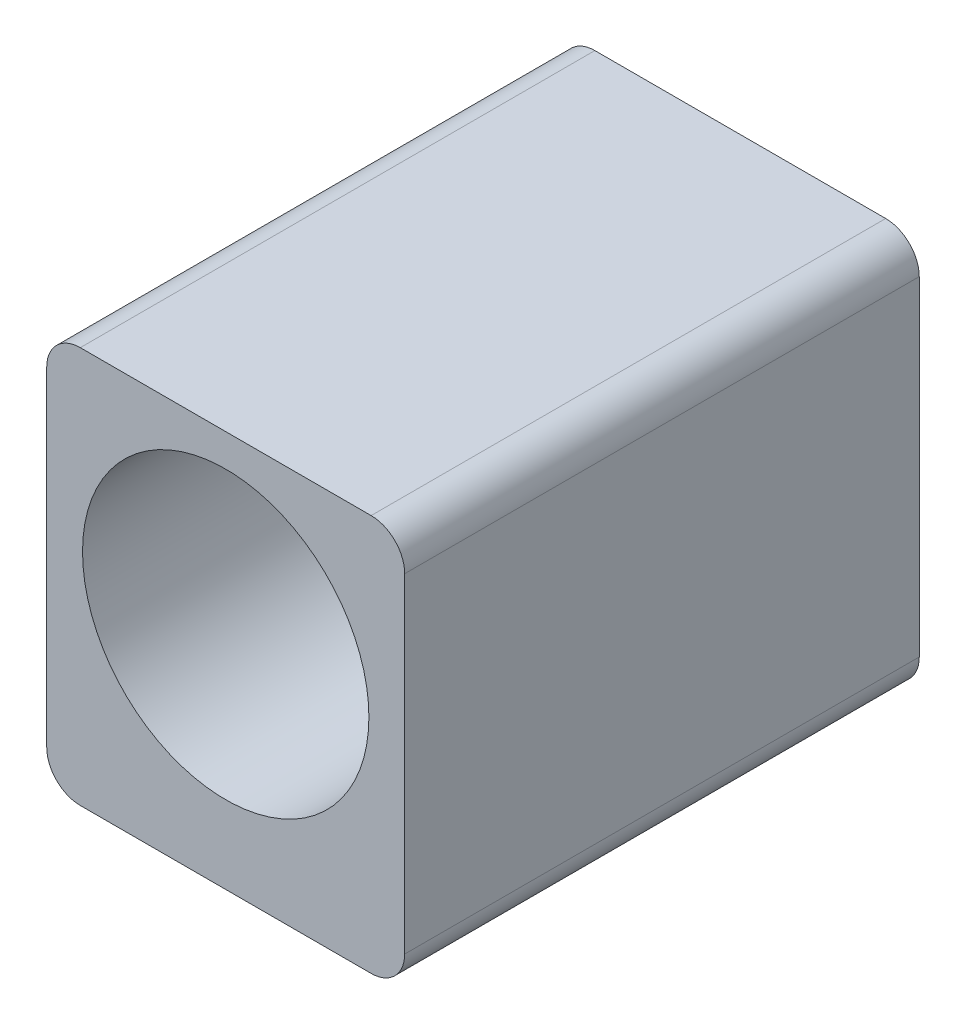
SolidWorks part; units mm, degrees
ref_plane "Front Plane" through (0, 0, 0) normal (0, 0, 1) x (1, 0, 0)
ref_plane "Top Plane" through (0, 0, 0) normal (0, 1, 0) x (1, 0, 0)
ref_plane "Right Plane" through (0, 0, 0) normal (1, 0, 0) x (0, 0, -1)
sketch "Sketch1" plane through (0, 0, 0) normal (0, 0, 1) x (1, 0, 0)
  line L0 (-13, -19.747) -> (13, -19.747)
  line L1 (16, -16.747) -> (16, 12.7)
  line L2 (13, 15.7) -> (-13, 15.7)
  line L3 (-16, 12.7) -> (-16, -16.747)
  arc A0 (13, -19.747) -> (16, -16.747) centre (13, -16.747) ccw
  arc A1 (16, 12.7) -> (13, 15.7) centre (13, 12.7) ccw
  arc A2 (-13, 15.7) -> (-16, 12.7) centre (-13, 12.7) ccw
  arc A3 (-16, -16.747) -> (-13, -19.747) centre (-13, -16.747) ccw
  circle A4 centre (0, 0) radius 12.8
extrude "Boss-Extrude1" add sketch "Sketch1" along normal mid plane 46
ref_plane "Plane1" through (0, -19.747, 0) normal (0, 1, 0) x (1, 0, 0)
sketch "Sketch2" plane through (0, -19.747, 0) normal (0, 1, 0) x (1, 0, 0)
  circle A0 centre (12, -17.5) radius 2
  circle A1 centre (-12, 17.5) radius 2
extrude "Cut-Extrude1" cut sketch "Sketch2" along normal blind 7.5
